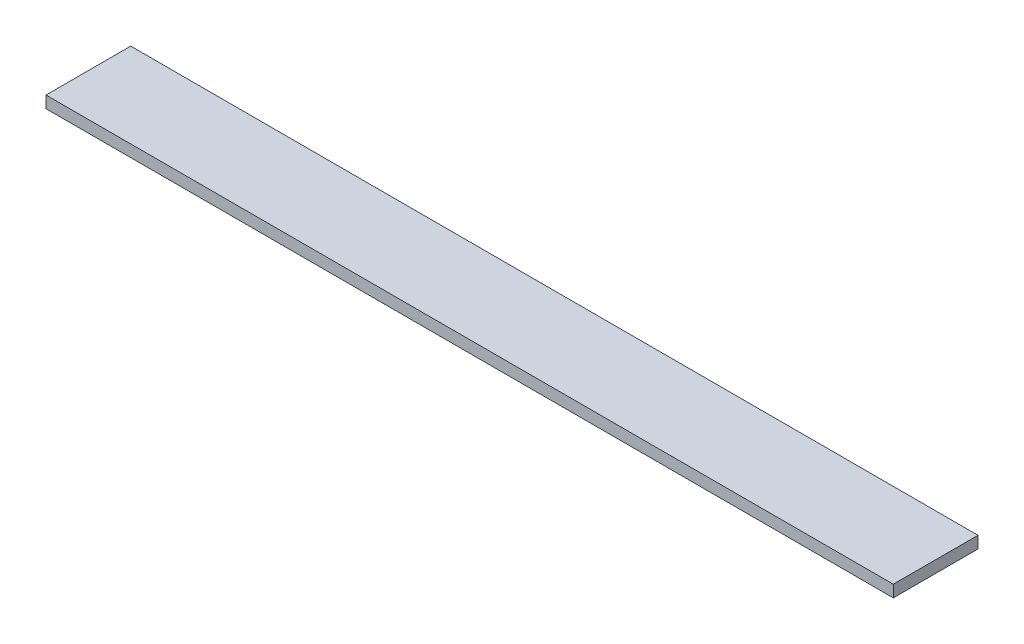
SolidWorks part; units mm, degrees
ref_plane "Front Plane" through (0, 0, 0) normal (0, 0, 1) x (1, 0, 0)
ref_plane "Top Plane" through (0, 0, 0) normal (0, 1, 0) x (1, 0, 0)
ref_plane "Right Plane" through (0, 0, 0) normal (1, 0, 0) x (0, 0, -1)
sketch "Sketch1" plane through (0, 0, 0) normal (0, 1, 0) x (1, 0, 0)
  line L1 (-25, -2.5) -> (25, -2.5)
  line L2 (-25, -2.5) -> (-25, 2.5)
  line L3 (-25, 2.5) -> (25, 2.5)
  line L4 (25, -2.5) -> (25, 2.5)
  line L5 (-25, -2.5) -> (25, 2.5) construction
  line L6 (-25, 2.5) -> (25, -2.5) construction
  point P0 (0, 0)
  dimension "D1" = 5
  dimension "D2" = 50
extrude "Boss-Extrude1" add sketch "Sketch1" along normal blind 0.7
